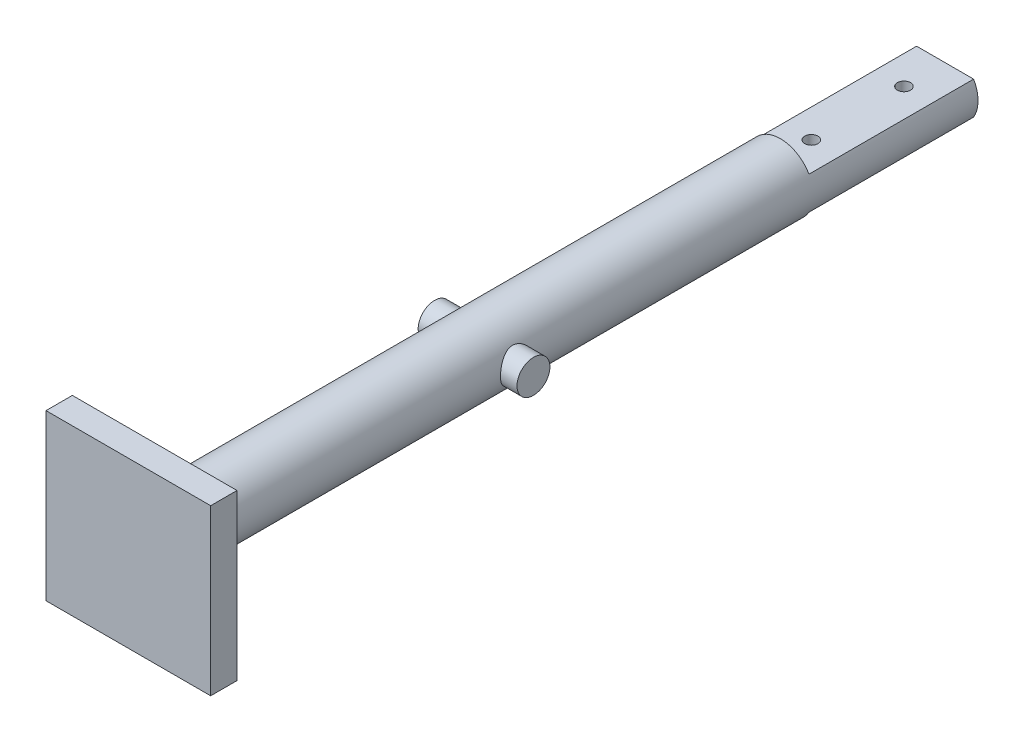
SolidWorks part; units mm, degrees
ref_plane "Front Plane" through (0, 0, 0) normal (0, 0, 1) x (1, 0, 0)
ref_plane "Top Plane" through (0, 0, 0) normal (0, 1, 0) x (1, 0, 0)
ref_plane "Right Plane" through (0, 0, 0) normal (1, 0, 0) x (0, 0, -1)
sketch "Sketch1" plane through (0, 0, 0) normal (0, 0, 1) x (1, 0, 0)
  circle A0 centre (0, 0) radius 12.7
sketch "Sketch9" plane through (0, 0, 0) normal (1, 0, 0) x (0, 0, -1)
  line L0 (0, 0) -> (-25.4, 0) construction
  circle A0 centre (-25.4, 0) radius 6.35
extrude "Boss-Extrude3" add sketch "Sketch1" along normal mid plane 304.8 contours A0
sketch "Sketch12" plane through (0, 0, 152.4) normal (0, 0, 1) x (1, 0, 0)
  line L1 (-31.75, 31.75) -> (31.75, 31.75)
  line L2 (-31.75, 31.75) -> (-31.75, -31.75)
  line L3 (-31.75, -31.75) -> (31.75, -31.75)
  line L4 (31.75, 31.75) -> (31.75, -31.75)
  line L5 (-31.75, 31.75) -> (31.75, -31.75) construction
  line L6 (-31.75, -31.75) -> (31.75, 31.75) construction
  point P0 (0, 0)
extrude "Boss-Extrude5" add sketch "Sketch12" along normal blind 10.16 contours L2 L3 L4 L1
ref_plane "Plane1" through (0, -6.35, 0) normal (0, 1, 0) x (1, 0, 0)
extrude "Boss-Extrude6" add sketch "Sketch9" along normal mid plane 38.1
ref_plane "Plane2" through (0, -6.35, 0) normal (0, 1, 0) x (1, 0, 0)
sketch "Sketch16" plane through (0, -6.35, 0) normal (0, 1, 0) x (1, 0, 0)
  line L0 (0, 0) -> (0, 152.4) construction
  line L1 (12.7, 152.4) -> (-12.7, 152.4) construction
  line L2 (0, 152.4) -> (-12.7, 152.4) construction
  line L3 (12.7, -19.0501) -> (12.7, 152.4) construction
  line L4 (-12.7, 152.4) -> (12.7, 152.4)
  line L5 (-12.7, 152.4) -> (-12.7, 88.9)
  line L6 (-12.7, 88.9) -> (12.7, 88.9)
  line L7 (12.7, 152.4) -> (12.7, 88.9)
extrude "Cut-Extrude2" cut sketch "Sketch16" against normal through all contours L5 L6 L7 L4
ref_plane "Plane3" through (0, 6.35, 0) normal (0, 1, 0) x (1, 0, 0)
sketch "Sketch17" plane through (0, 6.35, 0) normal (0, 1, 0) x (1, 0, 0)
  line L0 (12.7, -19.0501) -> (12.7, 152.4) construction
  line L1 (-12.7, 152.4) -> (12.7, 152.4)
  line L2 (-12.7, 152.4) -> (-12.7, 88.9)
  line L3 (-12.7, 88.9) -> (12.7, 88.9)
  line L4 (12.7, 152.4) -> (12.7, 88.9)
extrude "Cut-Extrude3" cut sketch "Sketch17" along normal through all
sketch "Sketch19" plane through (0, 6.35, 0) normal (0, 1, 0) x (1, 0, 0)
  line L0 (0, 88.9) -> (0, 100.8062) construction
  line L1 (-10.9985, 88.9) -> (10.9985, 88.9) construction
  line L2 (0, 103.3462) -> (0, 132.5562) construction
  line L3 (0, 132.5562) -> (0, 136.525) construction
  line L4 (10.9985, 88.9) -> (-10.9985, 88.9) construction
  line L5 (10.9985, 88.9) -> (-10.9985, 88.9) construction
  circle A0 centre (0, 100.8062) radius 2.54
  circle A1 centre (0, 136.525) radius 2.54
  dimension "D1" = 47.625
  dimension "D2" = 11.9063
extrude "Cut-Extrude5" cut sketch "Sketch19" against normal through all
sketch "Sketch20" plane through (0, -6.35, 0) normal (0, -1, 0) x (1, 0, 0)
  line L0 (0, -88.9) -> (0, -100.8062) construction
  line L1 (-10.9985, -88.9) -> (10.9985, -88.9) construction
  line L2 (0, -88.9) -> (0, -136.525) construction
  circle A0 centre (0, -100.8062) radius 2.54
  circle A1 centre (0, -136.525) radius 2.54
